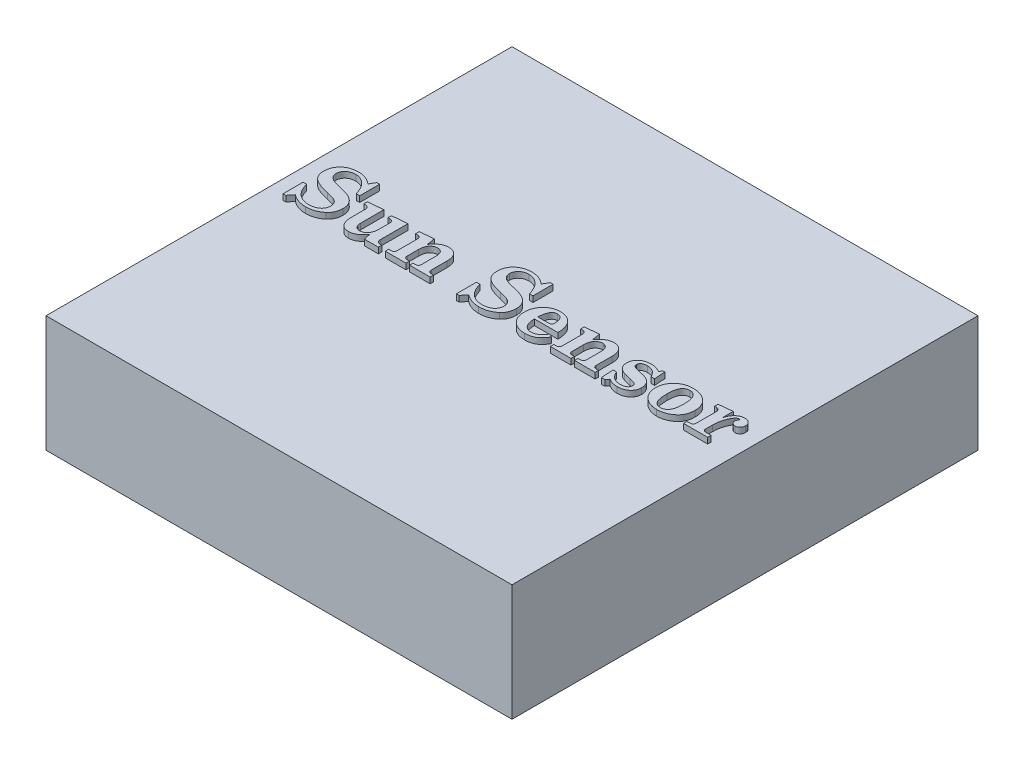
SolidWorks part; units mm, degrees
ref_plane "Front Plane" through (0, 0, 0) normal (0, 0, 1) x (1, 0, 0)
ref_plane "Top Plane" through (0, 0, 0) normal (0, 1, 0) x (1, 0, 0)
ref_plane "Right Plane" through (0, 0, 0) normal (1, 0, 0) x (0, 0, -1)
sketch "Sketch1" plane through (0, 0, 0) normal (0, 1, 0) x (1, 0, 0)
  line L1 (-40, 40) -> (40, 40)
  line L2 (-40, 40) -> (-40, -40)
  line L3 (-40, -40) -> (40, -40)
  line L4 (40, 40) -> (40, -40)
  line L5 (-40, 40) -> (40, -40) construction
  line L6 (-40, -40) -> (40, 40) construction
  point P0 (0, 0)
  dimension "D1" = 80
  dimension "D2" = 80
extrude "Boss-Extrude1" add sketch "Sketch1" along normal blind 20
sketch "Sketch3" plane through (0, 20, 0) normal (0, 1, 0) x (1, 0, 0)
  text T0 "<b>Sun Sensor</b>" font "@HYSWLongFangSong" height in points 36
extrude "Boss-Extrude2" add sketch "Sketch3" along normal blind 1
